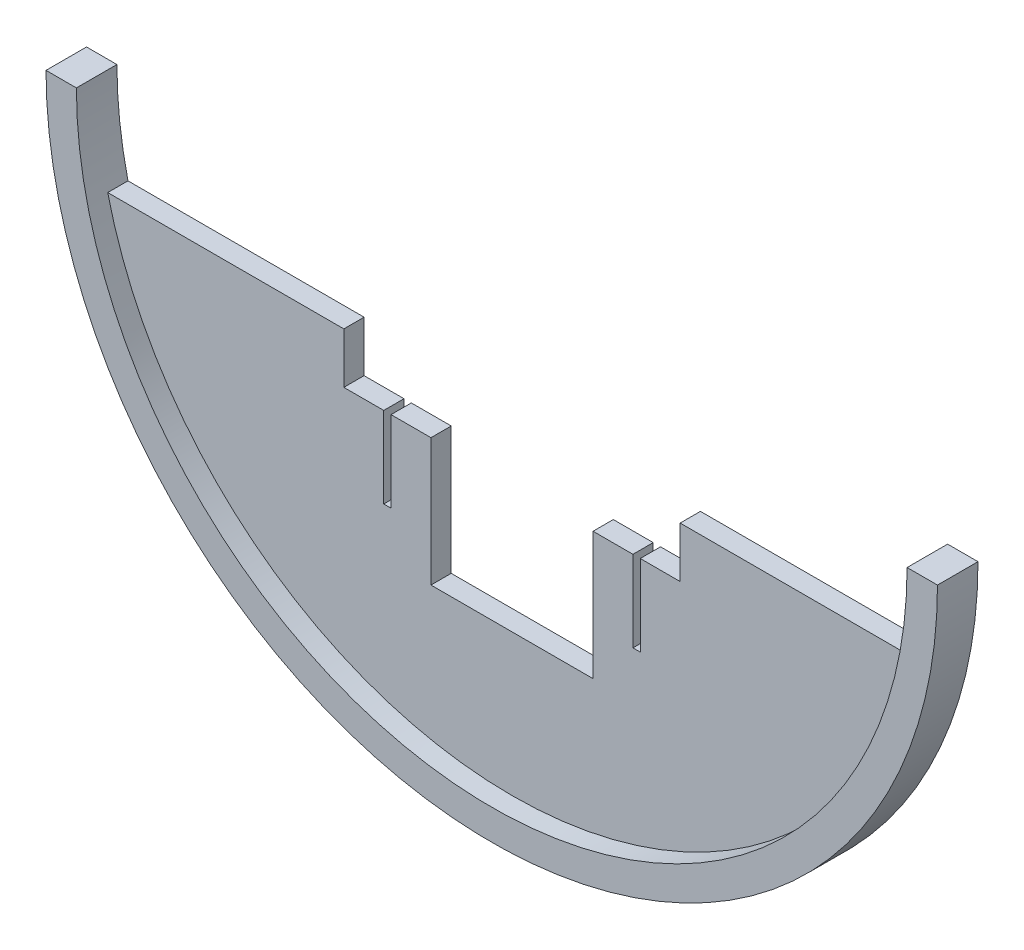
SolidWorks part; units mm, degrees
ref_plane "Alzado" through (0, 0, 0) normal (0, 0, 1) x (1, 0, 0)
ref_plane "Planta" through (0, 0, 0) normal (0, 1, 0) x (1, 0, 0)
ref_plane "Vista lateral" through (0, 0, 0) normal (1, 0, 0) x (0, 0, -1)
sketch "Sketch1" plane through (0, 0, 0) normal (0, 0, 1) x (1, 0, 0)
  line L1 (189.3701, -152.1799) -> (189.3701, -82.1799)
  line L2 (106.3701, 5.8201) -> (-10.1694, 5.8201)
  line L5 (149.3701, -82.1799) -> (229.3701, -82.1799)
  line L6 (149.3701, -82.1799) -> (149.3701, -19.1799)
  line L7 (149.3701, -19.1799) -> (129.6701, -19.1799)
  line L8 (106.3701, -19.1799) -> (106.3701, 5.8201)
  line L9 (-15.6299, 52.8201) -> (-30.6299, 52.8201)
  line L10 (394.3701, 52.8201) -> (409.3701, 52.8201)
  line L11 (189.3701, -152.1799) -> (189.3701, -167.1799) construction
  line L12 (229.3701, -82.1799) -> (229.3701, -19.1799)
  line L13 (229.3701, -19.1799) -> (249.0701, -19.1799)
  line L14 (272.3701, -19.1799) -> (272.3701, 5.8201)
  line L15 (272.3701, 5.8201) -> (388.9095, 5.8201)
  line L16 (126.0701, -19.1799) -> (126.0701, -59.1799)
  line L21 (129.6701, -19.1799) -> (129.6701, -59.1799)
  line L22 (126.0701, -59.1799) -> (129.6701, -59.1799)
  line L23 (126.0701, -19.1799) -> (106.3701, -19.1799)
  line L24 (252.6701, -19.1799) -> (272.3701, -19.1799)
  line L26 (249.0701, -19.1799) -> (249.0701, -59.1799)
  line L27 (249.0701, -59.1799) -> (252.6701, -59.1799)
  line L28 (252.6701, -19.1799) -> (252.6701, -59.1799)
  arc A1 (-15.6299, 52.8201) -> (394.3701, 52.8201) centre (189.3701, 52.8201) ccw
  arc A2 (-30.6299, 52.8201) -> (409.3701, 52.8201) centre (189.3701, 52.8201) ccw
  point P10 (189.3701, -82.1799)
  dimension "D2" = 205
  dimension "D4" = 80
  dimension "D1" = 70
  dimension "D3" = 15
  dimension "D5" = 63
  dimension "D6" = 43
  dimension "D7" = 15
  dimension "D8" = 25
  dimension "D9" = 15
  dimension "D10" = 43
  dimension "D11" = 40
  dimension "D12" = 3.6
  dimension "D13" = 3.6
extrude "Boss-Extrude1" add sketch "Sketch1" along normal blind 20 contours L2 A1 L1 L5 L6 L7 L8 | L1 A1 L15 L14 L13 L12 L5 | A1 L11 A2 L10 | L11 A1 L9 A2
sketch "Sketch2" plane through (0, 0, 20) normal (0, 0, 1) x (1, 0, 0)
  line L0 (-10.1694, 5.8201) -> (106.3701, 5.8201)
  line L1 (106.3701, 5.8201) -> (106.3701, -19.1799)
  line L2 (106.3701, -19.1799) -> (126.0701, -19.1799)
  line L3 (149.3701, -19.1799) -> (149.3701, -82.1799)
  line L4 (149.3701, -82.1799) -> (229.3701, -82.1799)
  line L6 (229.3701, -82.1799) -> (229.3701, -19.1799)
  line L7 (229.3701, -19.1799) -> (249.0701, -19.1799)
  line L8 (272.3701, -19.1799) -> (272.3701, 5.8201)
  line L9 (272.3701, 5.8201) -> (388.9095, 5.8201)
  line L10 (126.0701, -19.1799) -> (126.0701, -59.1799)
  line L11 (126.0701, -59.1799) -> (129.6701, -59.1799)
  line L12 (129.6701, -59.1799) -> (129.6701, -19.1799)
  line L13 (249.0701, -19.1799) -> (249.0701, -59.1799)
  line L14 (249.0701, -59.1799) -> (252.6701, -59.1799)
  line L15 (252.6701, -59.1799) -> (252.6701, -19.1799)
  line L16 (252.6701, -19.1799) -> (272.3701, -19.1799)
  line L17 (129.6701, -19.1799) -> (149.3701, -19.1799)
  arc A0 (-10.1694, 5.8201) -> (388.9095, 5.8201) centre (189.3701, 52.8201) ccw
extrude "Cut-Extrude2" cut sketch "Sketch2" against normal blind 10
